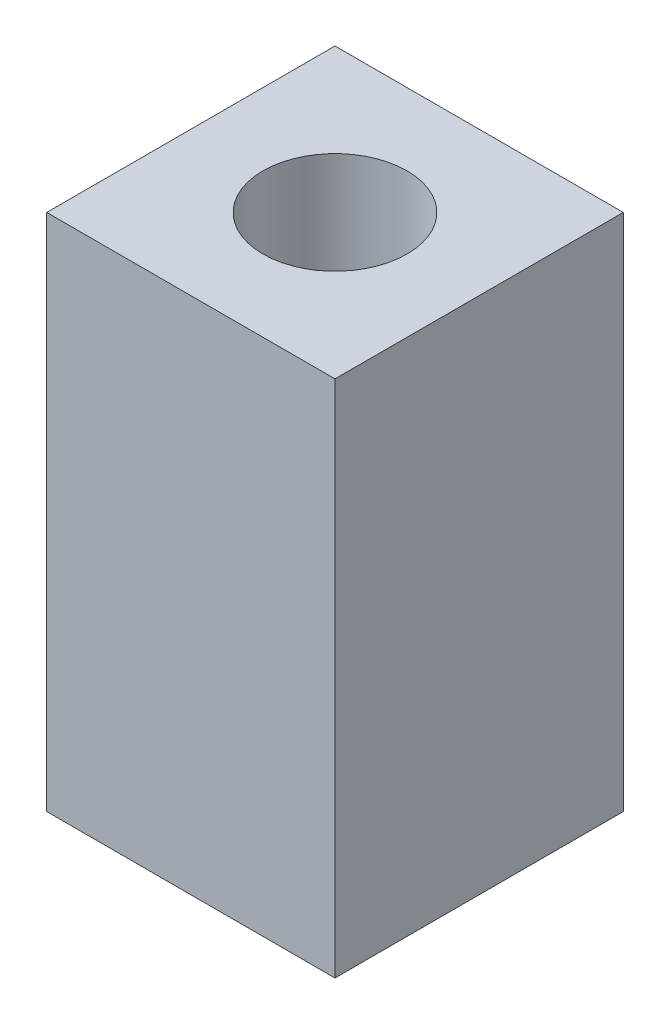
SolidWorks part; units mm, degrees
ref_plane "Спереди" through (0, 0, 0) normal (0, 0, 1) x (1, 0, 0)
ref_plane "Сверху" through (0, 0, 0) normal (0, 1, 0) x (1, 0, 0)
ref_plane "Справа" through (0, 0, 0) normal (1, 0, 0) x (0, 0, -1)
sketch "Эскиз1" plane through (0, 0, 0) normal (0, 1, 0) x (1, 0, 0)
  line L1 (-3, 3) -> (3, 3)
  line L2 (-3, 3) -> (-3, -3)
  line L3 (-3, -3) -> (3, -3)
  line L4 (3, 3) -> (3, -3)
  line L5 (-3, 3) -> (3, -3) construction
  line L6 (-3, -3) -> (3, 3) construction
  circle A0 centre (0, 0) radius 1.5
  point P0 (0, 0)
  dimension "D1" = 3
  dimension "D2" = 3
extrude "Бобышка-Вытянуть1" add sketch "Эскиз1" along normal blind 10.8
